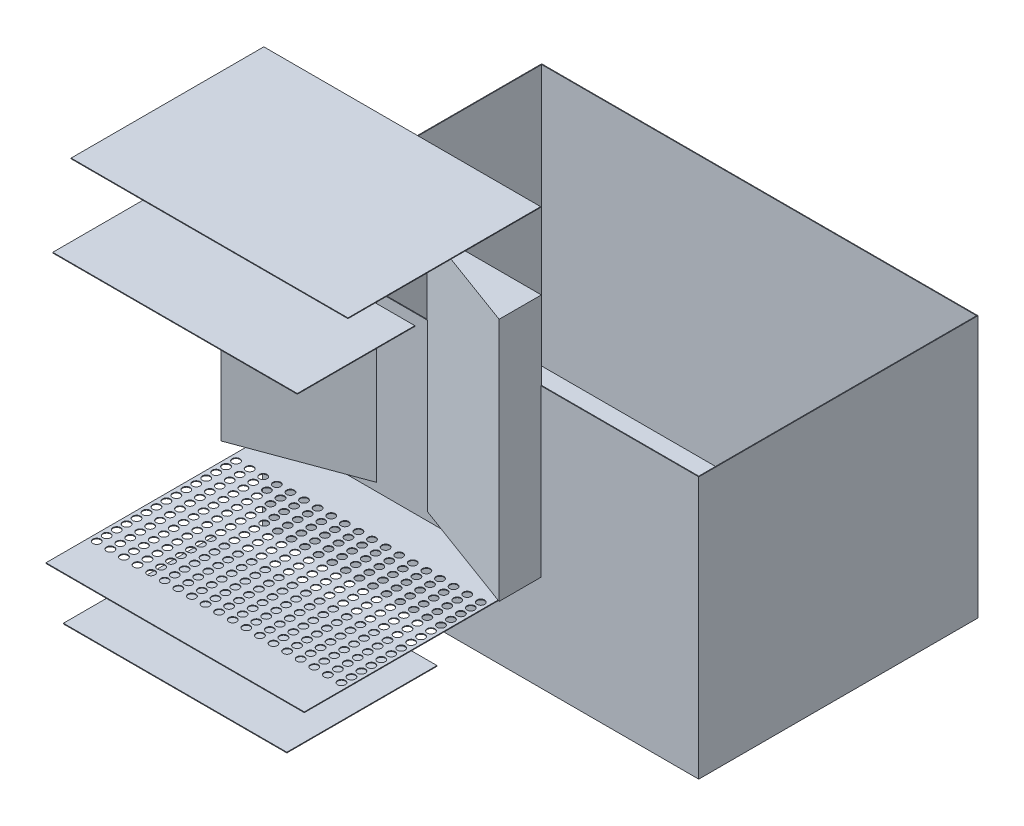
SolidWorks part; units mm, degrees
ref_plane "Спереди" through (0, 0, 0) normal (0, 0, 1) x (1, 0, 0)
ref_plane "Сверху" through (0, 0, 0) normal (0, 1, 0) x (1, 0, 0)
ref_plane "Справа" through (0, 0, 0) normal (1, 0, 0) x (0, 0, -1)
sketch "MASTER_FOOTPRINT" plane through (0, 0, 0) normal (0, 1, 0) x (1, 0, 0)
  line L1 (0, 0) -> (1250, 0)
  line L2 (0, 0) -> (0, 800)
  line L3 (0, 800) -> (1250, 800)
  line L4 (1250, 0) -> (1250, 800)
  dimension "D1" = 1250
  dimension "D2" = 800
extrude "BATH_BASE_PLATE" add sketch "MASTER_FOOTPRINT" along normal blind 750
shell "BATH_SHELL_2MM" thickness 2
sketch "Эскиз1" plane through (0, 0, 0) normal (0, 1, 0) x (1, 0, 0)
  line L1 (80, -220) -> (720, -220)
  line L2 (80, -220) -> (80, -650)
  line L3 (80, -650) -> (720, -650)
  line L4 (720, -220) -> (720, -650)
extrude "INLET_IMPACT_BAFFLE" add sketch "Эскиз1" along normal blind 2 from offset 125 separate body
sketch "Эскиз2" plane through (0, 0, 0) normal (0, 1, 0) x (1, 0, 0)
  line L0 (2, 2) -> (1248, 2) construction
  line L1 (30, 2) -> (770, 2)
  line L2 (30, 2) -> (30, -650)
  line L3 (30, -650) -> (770, -650)
  line L4 (770, 2) -> (770, -650)
  circle A0 centre (49.4737, -125) radius 11
  circle A1 centre (49.4737, -153.5) radius 11
  circle A2 centre (49.4737, -182) radius 11
  circle A3 centre (49.4737, -210.5) radius 11
  circle A4 centre (49.4737, -239) radius 11
  circle A5 centre (49.4737, -267.5) radius 11
  circle A6 centre (49.4737, -296) radius 11
  circle A7 centre (49.4737, -324.5) radius 11
  circle A8 centre (49.4737, -353) radius 11
  circle A9 centre (49.4737, -381.5) radius 11
  circle A10 centre (49.4737, -410) radius 11
  circle A11 centre (49.4737, -438.5) radius 11
  circle A12 centre (49.4737, -467) radius 11
  circle A13 centre (49.4737, -495.5) radius 11
  circle A14 centre (49.4737, -524) radius 11
  circle A15 centre (88.4211, -125) radius 11
  circle A16 centre (88.4211, -153.5) radius 11
  circle A17 centre (88.4211, -182) radius 11
  circle A18 centre (88.4211, -210.5) radius 11
  circle A19 centre (88.4211, -239) radius 11
  circle A20 centre (88.4211, -267.5) radius 11
  circle A21 centre (88.4211, -296) radius 11
  circle A22 centre (88.4211, -324.5) radius 11
  circle A23 centre (88.4211, -353) radius 11
  circle A24 centre (88.4211, -381.5) radius 11
  circle A25 centre (88.4211, -410) radius 11
  circle A26 centre (88.4211, -438.5) radius 11
  circle A27 centre (88.4211, -467) radius 11
  circle A28 centre (88.4211, -495.5) radius 11
  circle A29 centre (88.4211, -524) radius 11
  circle A30 centre (127.3684, -125) radius 11
  circle A31 centre (127.3684, -153.5) radius 11
  circle A32 centre (127.3684, -182) radius 11
  circle A33 centre (127.3684, -210.5) radius 11
  circle A34 centre (127.3684, -239) radius 11
  circle A35 centre (127.3684, -267.5) radius 11
  circle A36 centre (127.3684, -296) radius 11
  circle A37 centre (127.3684, -324.5) radius 11
  circle A38 centre (127.3684, -353) radius 11
  circle A39 centre (127.3684, -381.5) radius 11
  circle A40 centre (127.3684, -410) radius 11
  circle A41 centre (127.3684, -438.5) radius 11
  circle A42 centre (127.3684, -467) radius 11
  circle A43 centre (127.3684, -495.5) radius 11
  circle A44 centre (127.3684, -524) radius 11
  circle A45 centre (166.3158, -125) radius 11
  circle A46 centre (166.3158, -153.5) radius 11
  circle A47 centre (166.3158, -182) radius 11
  circle A48 centre (166.3158, -210.5) radius 11
  circle A49 centre (166.3158, -239) radius 11
  circle A50 centre (166.3158, -267.5) radius 11
  circle A51 centre (166.3158, -296) radius 11
  circle A52 centre (166.3158, -324.5) radius 11
  circle A53 centre (166.3158, -353) radius 11
  circle A54 centre (166.3158, -381.5) radius 11
  circle A55 centre (166.3158, -410) radius 11
  circle A56 centre (166.3158, -438.5) radius 11
  circle A57 centre (166.3158, -467) radius 11
  circle A58 centre (166.3158, -495.5) radius 11
  circle A59 centre (166.3158, -524) radius 11
  circle A60 centre (205.2632, -125) radius 11
  circle A61 centre (205.2632, -153.5) radius 11
  circle A62 centre (205.2632, -182) radius 11
  circle A63 centre (205.2632, -210.5) radius 11
  circle A64 centre (205.2632, -239) radius 11
  circle A65 centre (205.2632, -267.5) radius 11
  circle A66 centre (205.2632, -296) radius 11
  circle A67 centre (205.2632, -324.5) radius 11
  circle A68 centre (205.2632, -353) radius 11
  circle A69 centre (205.2632, -381.5) radius 11
  circle A70 centre (205.2632, -410) radius 11
  circle A71 centre (205.2632, -438.5) radius 11
  circle A72 centre (205.2632, -467) radius 11
  circle A73 centre (205.2632, -495.5) radius 11
  circle A74 centre (205.2632, -524) radius 11
  circle A75 centre (244.2105, -125) radius 11
  circle A76 centre (244.2105, -153.5) radius 11
  circle A77 centre (244.2105, -182) radius 11
  circle A78 centre (244.2105, -210.5) radius 11
  circle A79 centre (244.2105, -239) radius 11
  circle A80 centre (244.2105, -267.5) radius 11
  circle A81 centre (244.2105, -296) radius 11
  circle A82 centre (244.2105, -324.5) radius 11
  circle A83 centre (244.2105, -353) radius 11
  circle A84 centre (244.2105, -381.5) radius 11
  circle A85 centre (244.2105, -410) radius 11
  circle A86 centre (244.2105, -438.5) radius 11
  circle A87 centre (244.2105, -467) radius 11
  circle A88 centre (244.2105, -495.5) radius 11
  circle A89 centre (244.2105, -524) radius 11
  circle A90 centre (283.1579, -125) radius 11
  circle A91 centre (283.1579, -153.5) radius 11
  circle A92 centre (283.1579, -182) radius 11
  circle A93 centre (283.1579, -210.5) radius 11
  circle A94 centre (283.1579, -239) radius 11
  circle A95 centre (283.1579, -267.5) radius 11
  circle A96 centre (283.1579, -296) radius 11
  circle A97 centre (283.1579, -324.5) radius 11
  circle A98 centre (283.1579, -353) radius 11
  circle A99 centre (283.1579, -381.5) radius 11
  circle A100 centre (283.1579, -410) radius 11
  circle A101 centre (283.1579, -438.5) radius 11
  circle A102 centre (283.1579, -467) radius 11
  circle A103 centre (283.1579, -495.5) radius 11
  circle A104 centre (283.1579, -524) radius 11
  circle A105 centre (322.1053, -125) radius 11
  circle A106 centre (322.1053, -153.5) radius 11
  circle A107 centre (322.1053, -182) radius 11
  circle A108 centre (322.1053, -210.5) radius 11
  circle A109 centre (322.1053, -239) radius 11
  circle A110 centre (322.1053, -267.5) radius 11
  circle A111 centre (322.1053, -296) radius 11
  circle A112 centre (322.1053, -324.5) radius 11
  circle A113 centre (322.1053, -353) radius 11
  circle A114 centre (322.1053, -381.5) radius 11
  circle A115 centre (322.1053, -410) radius 11
  circle A116 centre (322.1053, -438.5) radius 11
  circle A117 centre (322.1053, -467) radius 11
  circle A118 centre (322.1053, -495.5) radius 11
  circle A119 centre (322.1053, -524) radius 11
  circle A120 centre (361.0526, -125) radius 11
  circle A121 centre (361.0526, -153.5) radius 11
  circle A122 centre (361.0526, -182) radius 11
  circle A123 centre (361.0526, -210.5) radius 11
  circle A124 centre (361.0526, -239) radius 11
  circle A125 centre (361.0526, -267.5) radius 11
  circle A126 centre (361.0526, -296) radius 11
  circle A127 centre (361.0526, -324.5) radius 11
  circle A128 centre (361.0526, -353) radius 11
  circle A129 centre (361.0526, -381.5) radius 11
  circle A130 centre (361.0526, -410) radius 11
  circle A131 centre (361.0526, -438.5) radius 11
  circle A132 centre (361.0526, -467) radius 11
  circle A133 centre (361.0526, -495.5) radius 11
  circle A134 centre (361.0526, -524) radius 11
  circle A135 centre (400, -125) radius 11
  circle A136 centre (400, -153.5) radius 11
  circle A137 centre (400, -182) radius 11
  circle A138 centre (400, -210.5) radius 11
  circle A139 centre (400, -239) radius 11
  circle A140 centre (400, -267.5) radius 11
  circle A141 centre (400, -296) radius 11
  circle A142 centre (400, -324.5) radius 11
  circle A143 centre (400, -353) radius 11
  circle A144 centre (400, -381.5) radius 11
  circle A145 centre (400, -410) radius 11
  circle A146 centre (400, -438.5) radius 11
  circle A147 centre (400, -467) radius 11
  circle A148 centre (400, -495.5) radius 11
  circle A149 centre (400, -524) radius 11
  circle A150 centre (438.9474, -125) radius 11
  circle A151 centre (438.9474, -153.5) radius 11
  circle A152 centre (438.9474, -182) radius 11
  circle A153 centre (438.9474, -210.5) radius 11
  circle A154 centre (438.9474, -239) radius 11
  circle A155 centre (438.9474, -267.5) radius 11
  circle A156 centre (438.9474, -296) radius 11
  circle A157 centre (438.9474, -324.5) radius 11
  circle A158 centre (438.9474, -353) radius 11
  circle A159 centre (438.9474, -381.5) radius 11
  circle A160 centre (438.9474, -410) radius 11
  circle A161 centre (438.9474, -438.5) radius 11
  circle A162 centre (438.9474, -467) radius 11
  circle A163 centre (438.9474, -495.5) radius 11
  circle A164 centre (438.9474, -524) radius 11
  circle A165 centre (477.8947, -125) radius 11
  circle A166 centre (477.8947, -153.5) radius 11
  circle A167 centre (477.8947, -182) radius 11
  circle A168 centre (477.8947, -210.5) radius 11
  circle A169 centre (477.8947, -239) radius 11
  circle A170 centre (477.8947, -267.5) radius 11
  circle A171 centre (477.8947, -296) radius 11
  circle A172 centre (477.8947, -324.5) radius 11
  circle A173 centre (477.8947, -353) radius 11
  circle A174 centre (477.8947, -381.5) radius 11
  circle A175 centre (477.8947, -410) radius 11
  circle A176 centre (477.8947, -438.5) radius 11
  circle A177 centre (477.8947, -467) radius 11
  circle A178 centre (477.8947, -495.5) radius 11
  circle A179 centre (477.8947, -524) radius 11
  circle A180 centre (516.8421, -125) radius 11
  circle A181 centre (516.8421, -153.5) radius 11
  circle A182 centre (516.8421, -182) radius 11
  circle A183 centre (516.8421, -210.5) radius 11
  circle A184 centre (516.8421, -239) radius 11
  circle A185 centre (516.8421, -267.5) radius 11
  circle A186 centre (516.8421, -296) radius 11
  circle A187 centre (516.8421, -324.5) radius 11
  circle A188 centre (516.8421, -353) radius 11
  circle A189 centre (516.8421, -381.5) radius 11
  circle A190 centre (516.8421, -410) radius 11
  circle A191 centre (516.8421, -438.5) radius 11
  circle A192 centre (516.8421, -467) radius 11
  circle A193 centre (516.8421, -495.5) radius 11
  circle A194 centre (516.8421, -524) radius 11
  circle A195 centre (555.7895, -125) radius 11
  circle A196 centre (555.7895, -153.5) radius 11
  circle A197 centre (555.7895, -182) radius 11
  circle A198 centre (555.7895, -210.5) radius 11
  circle A199 centre (555.7895, -239) radius 11
  circle A200 centre (555.7895, -267.5) radius 11
  circle A201 centre (555.7895, -296) radius 11
  circle A202 centre (555.7895, -324.5) radius 11
  circle A203 centre (555.7895, -353) radius 11
  circle A204 centre (555.7895, -381.5) radius 11
  circle A205 centre (555.7895, -410) radius 11
  circle A206 centre (555.7895, -438.5) radius 11
  circle A207 centre (555.7895, -467) radius 11
  circle A208 centre (555.7895, -495.5) radius 11
  circle A209 centre (555.7895, -524) radius 11
  circle A210 centre (594.7368, -125) radius 11
  circle A211 centre (594.7368, -153.5) radius 11
  circle A212 centre (594.7368, -182) radius 11
  circle A213 centre (594.7368, -210.5) radius 11
  circle A214 centre (594.7368, -239) radius 11
  circle A215 centre (594.7368, -267.5) radius 11
  circle A216 centre (594.7368, -296) radius 11
  circle A217 centre (594.7368, -324.5) radius 11
  circle A218 centre (594.7368, -353) radius 11
  circle A219 centre (594.7368, -381.5) radius 11
  circle A220 centre (594.7368, -410) radius 11
  circle A221 centre (594.7368, -438.5) radius 11
  circle A222 centre (594.7368, -467) radius 11
  circle A223 centre (594.7368, -495.5) radius 11
  circle A224 centre (594.7368, -524) radius 11
  circle A225 centre (633.6842, -125) radius 11
  circle A226 centre (633.6842, -153.5) radius 11
  circle A227 centre (633.6842, -182) radius 11
  circle A228 centre (633.6842, -210.5) radius 11
  circle A229 centre (633.6842, -239) radius 11
  circle A230 centre (633.6842, -267.5) radius 11
  circle A231 centre (633.6842, -296) radius 11
  circle A232 centre (633.6842, -324.5) radius 11
  circle A233 centre (633.6842, -353) radius 11
  circle A234 centre (633.6842, -381.5) radius 11
  circle A235 centre (633.6842, -410) radius 11
  circle A236 centre (633.6842, -438.5) radius 11
  circle A237 centre (633.6842, -467) radius 11
  circle A238 centre (633.6842, -495.5) radius 11
  circle A239 centre (633.6842, -524) radius 11
  circle A240 centre (672.6316, -125) radius 11
  circle A241 centre (672.6316, -153.5) radius 11
  circle A242 centre (672.6316, -182) radius 11
  circle A243 centre (672.6316, -210.5) radius 11
  circle A244 centre (672.6316, -239) radius 11
  circle A245 centre (672.6316, -267.5) radius 11
  circle A246 centre (672.6316, -296) radius 11
  circle A247 centre (672.6316, -324.5) radius 11
  circle A248 centre (672.6316, -353) radius 11
  circle A249 centre (672.6316, -381.5) radius 11
  circle A250 centre (672.6316, -410) radius 11
  circle A251 centre (672.6316, -438.5) radius 11
  circle A252 centre (672.6316, -467) radius 11
  circle A253 centre (672.6316, -495.5) radius 11
  circle A254 centre (672.6316, -524) radius 11
  circle A255 centre (711.5789, -125) radius 11
  circle A256 centre (711.5789, -153.5) radius 11
  circle A257 centre (711.5789, -182) radius 11
  circle A258 centre (711.5789, -210.5) radius 11
  circle A259 centre (711.5789, -239) radius 11
  circle A260 centre (711.5789, -267.5) radius 11
  circle A261 centre (711.5789, -296) radius 11
  circle A262 centre (711.5789, -324.5) radius 11
  circle A263 centre (711.5789, -353) radius 11
  circle A264 centre (711.5789, -381.5) radius 11
  circle A265 centre (711.5789, -410) radius 11
  circle A266 centre (711.5789, -438.5) radius 11
  circle A267 centre (711.5789, -467) radius 11
  circle A268 centre (711.5789, -495.5) radius 11
  circle A269 centre (711.5789, -524) radius 11
  circle A270 centre (750.5263, -125) radius 11
  circle A271 centre (750.5263, -153.5) radius 11
  circle A272 centre (750.5263, -182) radius 11
  circle A273 centre (750.5263, -210.5) radius 11
  circle A274 centre (750.5263, -239) radius 11
  circle A275 centre (750.5263, -267.5) radius 11
  circle A276 centre (750.5263, -296) radius 11
  circle A277 centre (750.5263, -324.5) radius 11
  circle A278 centre (750.5263, -353) radius 11
  circle A279 centre (750.5263, -381.5) radius 11
  circle A280 centre (750.5263, -410) radius 11
  circle A281 centre (750.5263, -438.5) radius 11
  circle A282 centre (750.5263, -467) radius 11
  circle A283 centre (750.5263, -495.5) radius 11
  circle A284 centre (750.5263, -524) radius 11
extrude "DISTRIBUTOR_D22" add sketch "Эскиз2" along normal blind 2 from offset 250 separate body
sketch "Эскиз3" plane through (0, 0, 0) normal (0, 1, 0) x (1, 0, 0)
  line L0 (30, -650) -> (770, -650) construction
  line L1 (49.4737, -313.5) -> (750, -313.5)
  line L2 (49.4737, -313.5) -> (49.4737, -650)
  line L3 (49.4737, -650) -> (750, -650)
  line L4 (750, -313.5) -> (750, -650)
  circle A0 centre (49.4737, -324.5) radius 11 construction
extrude "OUTLET_SUBMERGED_BAFFLE" add sketch "Эскиз3" along normal blind 2 from offset 1030 separate body
sketch "Эскиз4" plane through (0, 0, 0) normal (0, 1, 0) x (1, 0, 0)
  line L1 (2, 2) -> (795, 2)
  line L2 (2, 2) -> (2, -550)
  line L3 (2, -550) -> (795, -550)
  line L4 (795, 2) -> (795, -550)
extrude "OVERFLOW_WEIR_Z550" add sketch "Эскиз4" along normal blind 2 from offset 1190 separate body
sketch "Эскиз5" plane through (0, 0, 0) normal (0, 1, 0) x (1, 0, 0)
  line L0 (2, 1) -> (2, -120)
  line L1 (2, -120) -> (330, 1)
  line L2 (330, 1) -> (2, 1)
  line L3 (798, 1) -> (798, -120)
  line L4 (798, -120) -> (470, 1)
  line L5 (470, 1) -> (798, 1)
extrude "SLOPED_SEDIMENT_FLOOR" add sketch "Эскиз5" along normal blind 700 from offset 275
equation "\"AI_Q_Peak\"= 0.006"
equation "\"AI_B_Bath\" = 800"
equation "\"AI_L_Settle\" = 800"
equation "\"AI_L_Inlet\"= 250"
equation "\"AI_L_Outlet\"= 200"
equation "\"AI_L_Bath\" = 1250"
equation "\"AI_H_Water\"= 550"
equation "\"AI_H_Freeboard\"= 200"
equation "\"AI_H_Bath\"= 750"
equation "\"AI_Shell_Thickness\"= 2"
equation "\"AI_Inlet_DN\"= 100"
equation "\"AI_Weir_Width\"= 600"
equation "\"AI_Inlet_Baffle_Offset\"= 125"
equation "\"AI_Distributor_Open_Area\"= 0.28"
equation "\"AI_Distributor_Hole_Dia\"= 22"
equation "\"AI_Distributor_Blind_Zone\"= 110"
equation "\"AI_Outlet_Baffle_Depth\"= 250"
equation "\"AI_Screw_Diameter\"= 100"
equation "\"AI_Screw_Pitch\"= 100"
equation "\"AI_Screw_Angle\"= 30"
equation "\"AI_Screw_Rpm\"= 15"
equation "\"AI_Screw_Clearance\"= 5"
equation "\"AI_Liner_Thickness\"= 5"
equation "\"AI_Discharge_Height\"= 650"
equation "\"AI_Frame_Height\"= 500"
equation "\"D1@MASTER_FOOTPRINT\" = \"AI_L_Bath\""
equation "\"D2@MASTER_FOOTPRINT\" = \"AI_B_Bath\""
equation "\"D1@BATH_BASE_PLATE\" = \"AI_H_Bath\""
